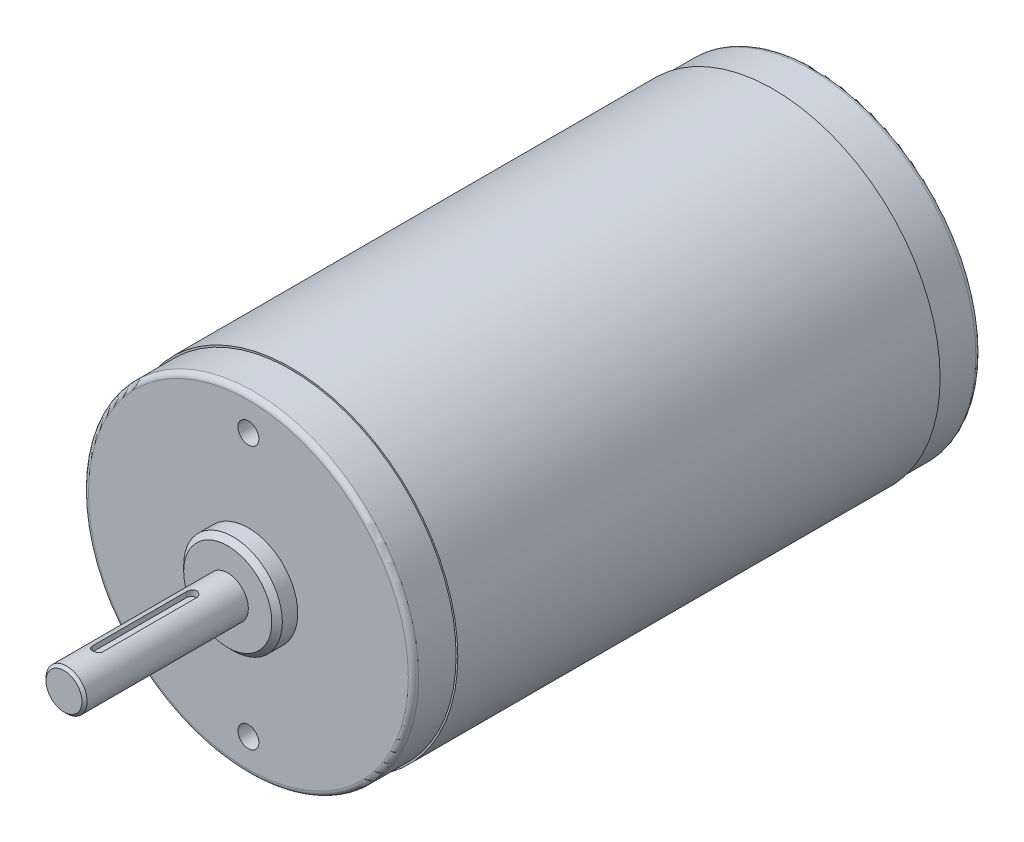
SolidWorks part; units mm, degrees
material "6061-T6 (SS)"
ref_plane "Front Plane" through (0, 0, 0) normal (0, 0, 1) x (1, 0, 0)
ref_plane "Top Plane" through (0, 0, 0) normal (0, 1, 0) x (1, 0, 0)
ref_plane "Right Plane" through (0, 0, 0) normal (1, 0, 0) x (0, 0, -1)
sketch "Sketch1" plane through (0, 0, 0) normal (1, 0, 0) x (0, 0, -1)
  line L0 (-31.623, 0) -> (-31.623, 3.9751)
  line L1 (-31.623, 3.9751) -> (0, 3.9751)
  line L2 (0, 3.9751) -> (0, 9.525)
  line L3 (0, 9.525) -> (3.9878, 9.525)
  line L4 (3.9878, 9.525) -> (3.9878, 31.877)
  line L5 (3.9878, 31.877) -> (12.2174, 31.877)
  line L6 (12.2174, 31.877) -> (12.2174, 32.2072)
  line L7 (12.2174, 32.2072) -> (105.3592, 32.2072)
  line L8 (105.3592, 32.2072) -> (105.3592, 31.877)
  line L9 (105.3592, 31.877) -> (113.5888, 31.877)
  line L10 (113.5888, 31.877) -> (113.5888, 15.0368)
  line L11 (113.5888, 15.0368) -> (118.5888, 15.0368)
  line L12 (118.5888, 15.0368) -> (118.5888, 0)
  line L13 (118.5888, 0) -> (-31.623, 0)
  line L14 (-111.8665, 0) -> (217.4307, 0) construction
  dimension "D1" = 109.601
  dimension "D2" = 64.4144
  dimension "D3" = 3.9878
  dimension "D4" = 35.6108
  dimension "D5" = 19.05
  dimension "D6" = 7.9502
  dimension "D7" = 63.754
  dimension "D8" = 8.2296
  dimension "D9" = 30.0736
  dimension "D10" = 5
revolve "Revolve1" add sketch "Sketch1" angle 360 about L14
fillet "Fillet1" radius 1 2 edges at (31.877, 0, -113.5888) (31.877, 0, -3.9878)
chamfer "Chamfer1" distance 1.016 angle 45 2 edges at (15.0368, 0, -118.5888) (9.525, 0, 0)
chamfer "Chamfer2" distance 0.5 angle 45 1 edges at (3.9751, 0, 31.623)
hole_wizard "#10-32 Tapped Hole1" positions "Sketch3" profile "Sketch2" tap size "#10-32" standard "ANSI Inch"
sketch "Sketch3" plane through (0, 0, 0) normal (0, 0, 1) x (1, 0, 0)
  circle A0 centre (0, 0) radius 25.4
  point P0 (0, 25.4)
  point P2 (0, -25.4)
  dimension "D1" = 50.8
sketch "Sketch2" plane through (0, 25.4, 0) normal (1, 0, 0) x (0, -1, 0)
  line L0 (0, 0) -> (0, 14.8277)
  line L1 (0, 14.8277) -> (2.0193, 13.6144)
  line L2 (2.0193, 13.6144) -> (2.0193, 0)
  line L5 (2.0193, 0) -> (0, 0)
  line L10 (0, 14.8277) -> (-2.0193, 13.6144) construction
  line L11 (0, -6.35) -> (0, 107.95) construction
  dimension "Tap Drill Dia." = 4.0386
  dimension "Tap Drill Depth" = 13.6144
  dimension "Drill Angle" = 118
cosmetic thread "Hole Thread1" parameters "D1"=9.652, "D2"=4.826
cosmetic thread "Hole Thread2" parameters "D1"=9.652, "D2"=4.826
ref_plane "Plane1" through (0, -3.9751, 0) normal (0, -1, 0) x (-1, 0, 0)
sketch "Sketch4" plane through (0, -3.9751, 0) normal (0, -1, 0) x (-1, 0, 0)
  line L0 (0, -6.9939) -> (0, -25.0939) construction
  line L1 (0.9995, -6.9939) -> (0.9995, -25.0939)
  line L2 (-0.9995, -6.9939) -> (-0.9995, -25.0939)
  line L6 (-8.509, 0) -> (8.509, 0) construction
  arc A0 (0.9995, -6.9939) -> (-0.9995, -6.9939) centre (0, -6.9939) ccw
  arc A1 (-0.9995, -25.0939) -> (0.9995, -25.0939) centre (0, -25.0939) ccw
  point P3 (0, -16.0439)
  dimension "D1" = 20.099
  dimension "D2" = 1.999
  dimension "D3" = 5.9944
extrude "Cut-Extrude1" cut sketch "Sketch4" against normal through all from offset 6.7996 offset against normal yes
sketch "Sketch5" plane through (0, 0, -113.5888) normal (0, 0, -1) x (-1, 0, 0)
  line L0 (0, 0) -> (0, 36.4051) construction
  line L1 (0, 0) -> (11.1851, 18.6151) construction
  line L2 (0, 0) -> (18.6151, 11.1851) construction
  circle A0 centre (11.1851, 18.6151) radius 4.318
  circle A1 centre (18.6151, 11.1851) radius 4.318
  dimension "D1" = 8.636
  dimension "D2" = 31
  dimension "D3" = 28
  dimension "D4" = 21.717
extrude "Boss-Extrude1" add sketch "Sketch5" along normal blind 2.2606 draft 45
